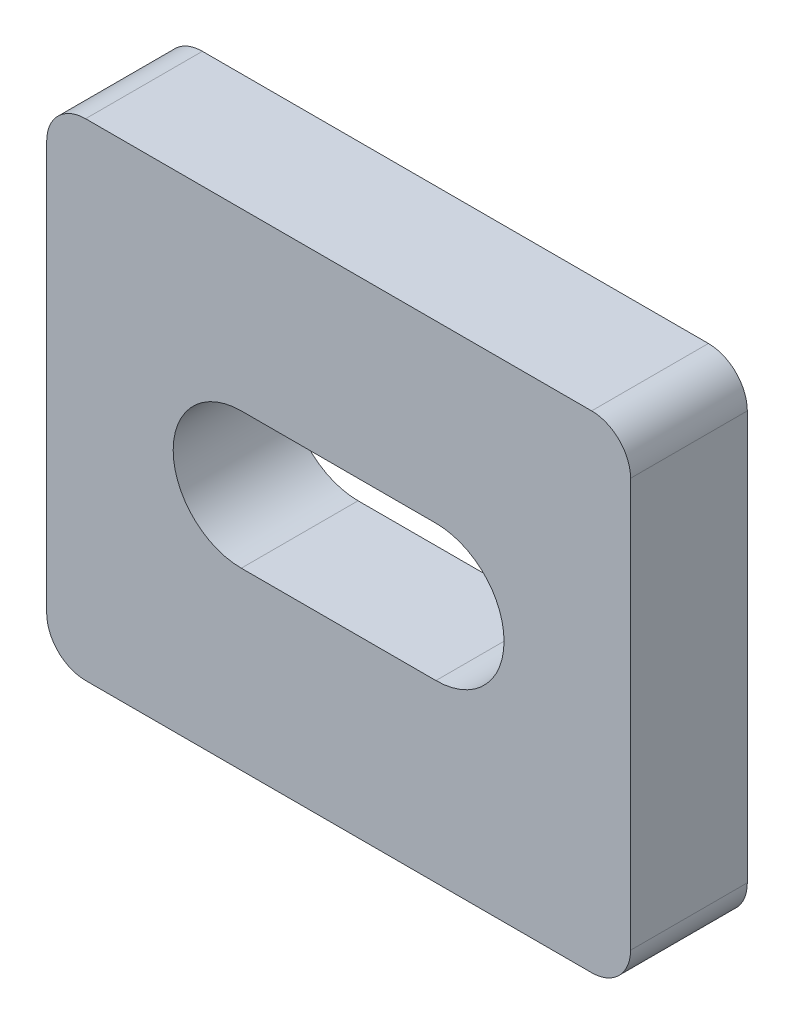
SolidWorks part; units mm, degrees
ref_plane "정면" through (0, 0, 0) normal (0, 0, 1) x (1, 0, 0)
ref_plane "윗면" through (0, 0, 0) normal (0, 1, 0) x (1, 0, 0)
ref_plane "우측면" through (0, 0, 0) normal (1, 0, 0) x (0, 0, -1)
sketch "스케치1" plane through (0, 0, 0) normal (0, 0, 1) x (1, 0, 0)
  line L0 (0, 0) -> (18.3923, 0) construction
  line L1 (0, 0) -> (0, 12.5746) construction
  line L2 (-5, 3.5) -> (5, 3.5)
  line L3 (-15, -12.5) -> (15, -12.5)
  line L4 (-15, -12.5) -> (-15, 12.5)
  line L5 (-15, 12.5) -> (15, 12.5)
  line L6 (15, -12.5) -> (15, 12.5)
  line L7 (-15, -12.5) -> (15, 12.5) construction
  line L8 (-15, 12.5) -> (15, -12.5) construction
  line L9 (-5, -3.5) -> (5, -3.5)
  circle A0 centre (5, 0) radius 3.5
  circle A1 centre (-5, 0) radius 3.5
  point P16 (0, 0)
  point P17 (0, 0)
  dimension "D3" = 7
  dimension "D4" = 7
  dimension "D1" = 30
  dimension "D2" = 25
  dimension "D5" = 10
  dimension "D6" = 5
extrude "보스-돌출2" add sketch "스케치1" along normal blind 6 contours L3 L6 L5 L4 A1 L2 A0 L9
fillet "필렛2" radius 2 4 edges at (-15, 12.5, 3) (15, 12.5, 3) (15, -12.5, 3) (-15, -12.5, 3)
